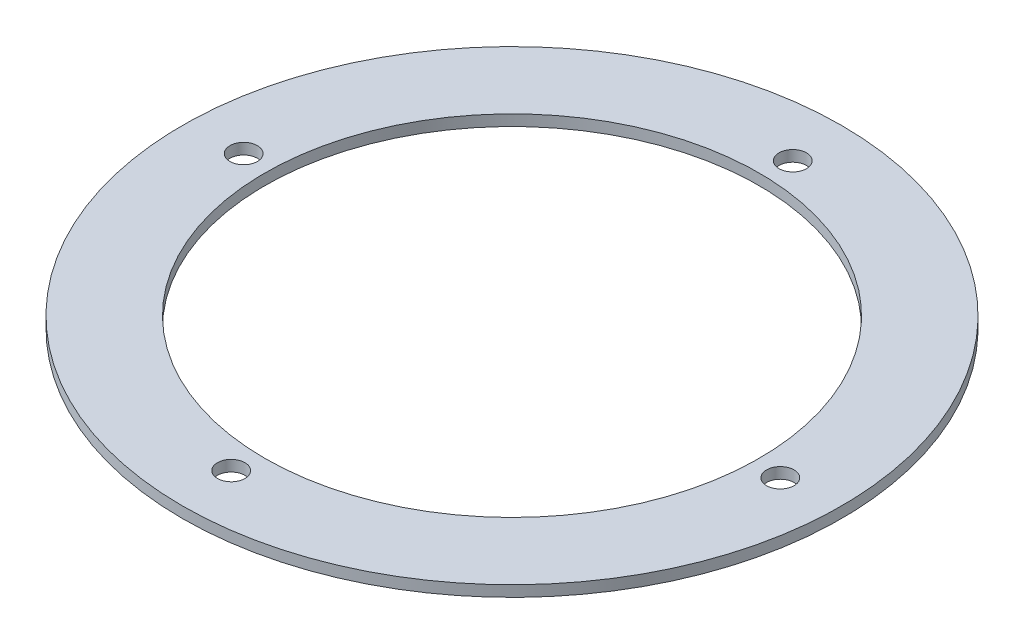
SolidWorks part; units mm, degrees
ref_plane "前视基准面" through (0, 0, 0) normal (0, 0, 1) x (1, 0, 0)
ref_plane "上视基准面" through (0, 0, 0) normal (0, 1, 0) x (1, 0, 0)
ref_plane "右视基准面" through (0, 0, 0) normal (1, 0, 0) x (0, 0, -1)
sketch "草图1" plane through (0, 0, 0) normal (0, 1, 0) x (1, 0, 0)
  line L0 (0, 0) -> (1.4851, 65.4982) construction
  circle A0 centre (0, 0) radius 60
  circle A1 centre (0, 0) radius 45
  circle A2 centre (0, 0) radius 50 construction
  circle A3 centre (1.1334, 49.9872) radius 2.5
  circle A4 centre (49.9872, -1.1334) radius 2.5
  circle A5 centre (-1.1334, -49.9872) radius 2.5
  circle A6 centre (-49.9872, 1.1334) radius 2.5
  point P18 (0, 0)
  dimension "D1" = 120
  dimension "D2" = 90
  dimension "D3" = 100
  dimension "D4" = 5
  dimension "D5" = 4
extrude "凸台-拉伸1" add sketch "草图1" along normal blind 2
